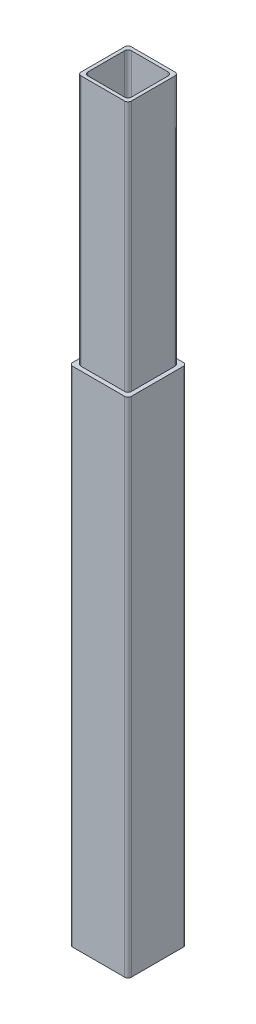
SolidWorks part; units mm, degrees
material "1.0037 (S235JR)"
ref_plane "Plan de face" through (0, 0, 0) normal (0, 0, 1) x (1, 0, 0)
ref_plane "Plan de dessus" through (0, 0, 0) normal (0, 1, 0) x (1, 0, 0)
ref_plane "Plan de droite" through (0, 0, 0) normal (1, 0, 0) x (0, 0, -1)
sketch "Esquisse1" plane through (0, 0, 0) normal (0, 0, 1) x (1, 0, 0)
  line L0 (0, 0) -> (0, 300)
  line L1 (0, 300) -> (0, 200)
  line L2 (0, 200) -> (0, 450)
  dimension "D1" = 300
  dimension "D2" = 150
  dimension "D3" = 100
other "Custom TUBE-CARRE-35-2.5(1)"
ref_plane "Plan1" through (0, 0, 0) normal (0, 1, 0) x (-1, 0, 0)
sketch "Esquisse11" plane through (0, 0, 0) normal (0, 1, 0) x (-1, 0, 0)
  line L1 (-13, -15) -> (13, -15)
  line L2 (-15, -13) -> (-15, 13)
  line L3 (-13, 15) -> (13, 15)
  line L4 (15, -13) -> (15, 13)
  line L5 (-15, -15) -> (15, 15) construction
  line L6 (-15, 15) -> (15, -15) construction
  line L7 (-15.5, -17.5) -> (15.5, -17.5)
  line L8 (-17.5, -15.5) -> (-17.5, 15.5)
  line L9 (-15.5, 17.5) -> (15.5, 17.5)
  line L10 (17.5, -15.5) -> (17.5, 15.5)
  line L11 (-17.5, -17.5) -> (17.5, 17.5) construction
  line L12 (-17.5, 17.5) -> (17.5, -17.5) construction
  arc A0 (15.5, -17.5) -> (17.5, -15.5) centre (15.5, -15.5) ccw
  arc A1 (13, -15) -> (15, -13) centre (13, -13) ccw
  arc A2 (-13, -15) -> (-15, -13) centre (-13, -13) cw
  arc A3 (-15.5, -17.5) -> (-17.5, -15.5) centre (-15.5, -15.5) cw
  arc A4 (15.5, 17.5) -> (17.5, 15.5) centre (15.5, 15.5) cw
  arc A5 (13, 15) -> (15, 13) centre (13, 13) cw
  arc A6 (-15, 13) -> (-13, 15) centre (-13, 13) cw
  arc A7 (-17.5, 15.5) -> (-15.5, 17.5) centre (-15.5, 15.5) cw
  point P0 (0, 0)
  point P6 (0, 0)
  point P35 (0, 17.5)
  point P36 (0, 15)
  point P37 (-15, 0)
  point P38 (-17.5, 0)
  point P39 (0, -15)
  point P40 (0, -17.5)
  point P41 (15, 0)
  point P42 (17.5, 0)
  point P43 (0, 0)
  dimension "D5" = 2
  dimension "D1" = 2.5
  dimension "D2" = 35
  dimension "D3" = 35
  dimension "D4" = 2.5
other "Custom TUBE-CARRE-30-2(1)"
ref_plane "Plan2" through (0, 200, 0) normal (0, 1, 0) x (-1, 0, 0)
sketch "Esquisse12" plane through (0, 200, 0) normal (0, 1, 0) x (-1, 0, 0)
  line L1 (-11, -13) -> (11, -13)
  line L2 (-13, -11) -> (-13, 11)
  line L3 (-11, 13) -> (11, 13)
  line L4 (13, -11) -> (13, 11)
  line L5 (-13, -13) -> (13, 13) construction
  line L6 (-13, 13) -> (13, -13) construction
  line L7 (-13, -15) -> (13, -15)
  line L8 (-15, -13) -> (-15, 13)
  line L9 (-13, 15) -> (13, 15)
  line L10 (15, -13) -> (15, 13)
  line L11 (-15, -15) -> (15, 15) construction
  line L12 (-15, 15) -> (15, -15) construction
  arc A0 (13, -15) -> (15, -13) centre (13, -13) ccw
  arc A1 (11, -13) -> (13, -11) centre (11, -11) ccw
  arc A2 (-11, -13) -> (-13, -11) centre (-11, -11) cw
  arc A3 (-13, -15) -> (-15, -13) centre (-13, -13) cw
  arc A4 (13, 15) -> (15, 13) centre (13, 13) cw
  arc A5 (11, 13) -> (13, 11) centre (11, 11) cw
  arc A6 (-13, 11) -> (-11, 13) centre (-11, 11) cw
  arc A7 (-15, 13) -> (-13, 15) centre (-13, 13) cw
  point P0 (0, 0)
  point P6 (0, 0)
  point P35 (0, 15)
  point P36 (0, 13)
  point P37 (-13, 0)
  point P38 (-15, 0)
  point P39 (0, -15)
  point P40 (0, -13)
  point P41 (15, 0)
  point P42 (13, 0)
  point P43 (0, 0)
  point P44 (0, 0)
  dimension "D5" = 2
  dimension "D1" = 2
  dimension "D2" = 30
  dimension "D3" = 30
  dimension "D4" = 2
